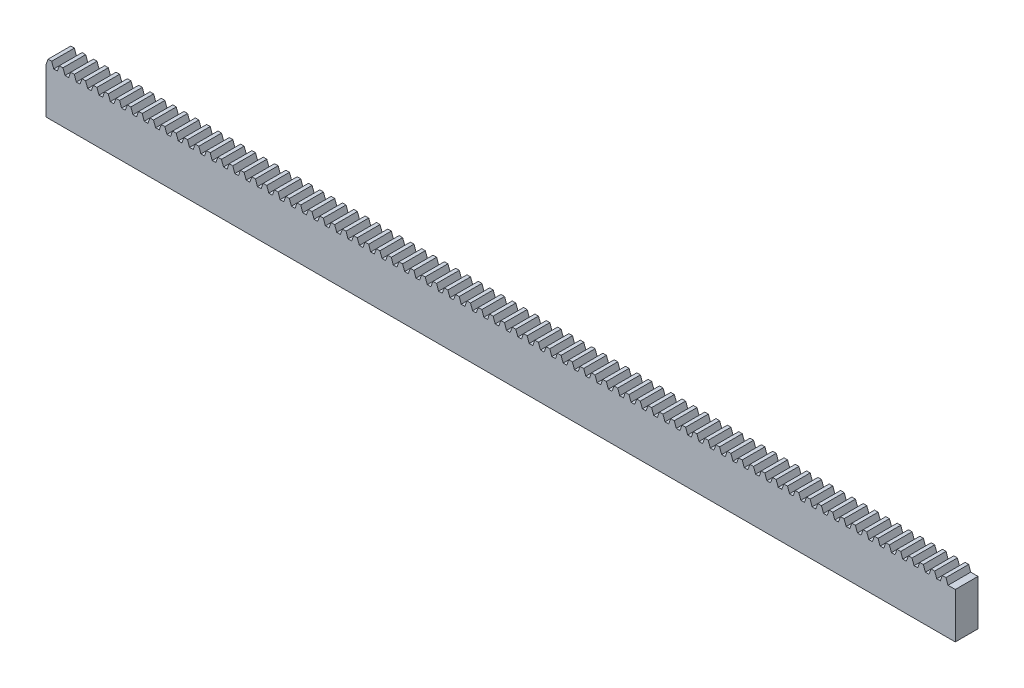
SolidWorks part; units mm, degrees
ref_plane "前视基准面" through (0, 0, 0) normal (0, 0, 1) x (1, 0, 0)
ref_plane "上视基准面" through (0, 0, 0) normal (0, 1, 0) x (1, 0, 0)
ref_plane "右视基准面" through (0, 0, 0) normal (1, 0, 0) x (0, 0, -1)
sketch "草图1" plane through (0, 0, 0) normal (0, 0, 1) x (1, 0, 0)
  line L1 (0, 0) -> (200, 0)
  line L2 (0, 0) -> (0, -10)
  line L3 (0, -10) -> (200, -10)
  line L4 (200, 0) -> (200, -10)
  dimension "D1" = 10
  dimension "L" = 200
extrude "拉伸1" add sketch "草图1" along normal blind 5
sketch "草图2" plane through (0, 0, 5) normal (0, 0, 1) x (1, 0, 0)
  line L0 (0, 0) -> (0.8189, 2.25)
  line L1 (0.8189, 2.25) -> (0.8764, 2.25)
  line L2 (0.8764, 2.25) -> (1.6953, 0)
  line L3 (200, 0) -> (0, 0) construction
  line L4 (0, 0) -> (1.6953, 0)
  line L5 (0.455, 1.25) -> (1.2404, 1.25) construction
  line L6 (0.455, 1.25) -> (1.2404, 1.25)
  line M4 (200, 0) -> (0, 0)
  dimension "D2" = 70
  dimension "alpha" = 110
  dimension "ha" = 1
  dimension "hf" = 1.25
  dimension "S" = 0.7854
extrude "拉伸2" add sketch "草图2" against normal up to surface (5 mm away) contours L6 L0 L2 M4 up to face at (100, -5, 0)
pattern_linear "阵列(线性)1" count 80 spacing 2.49 along (1, 0, 0) of "拉伸2"
equation "\"D2@草图2\" = 180 - \"alpha@草图2\""
